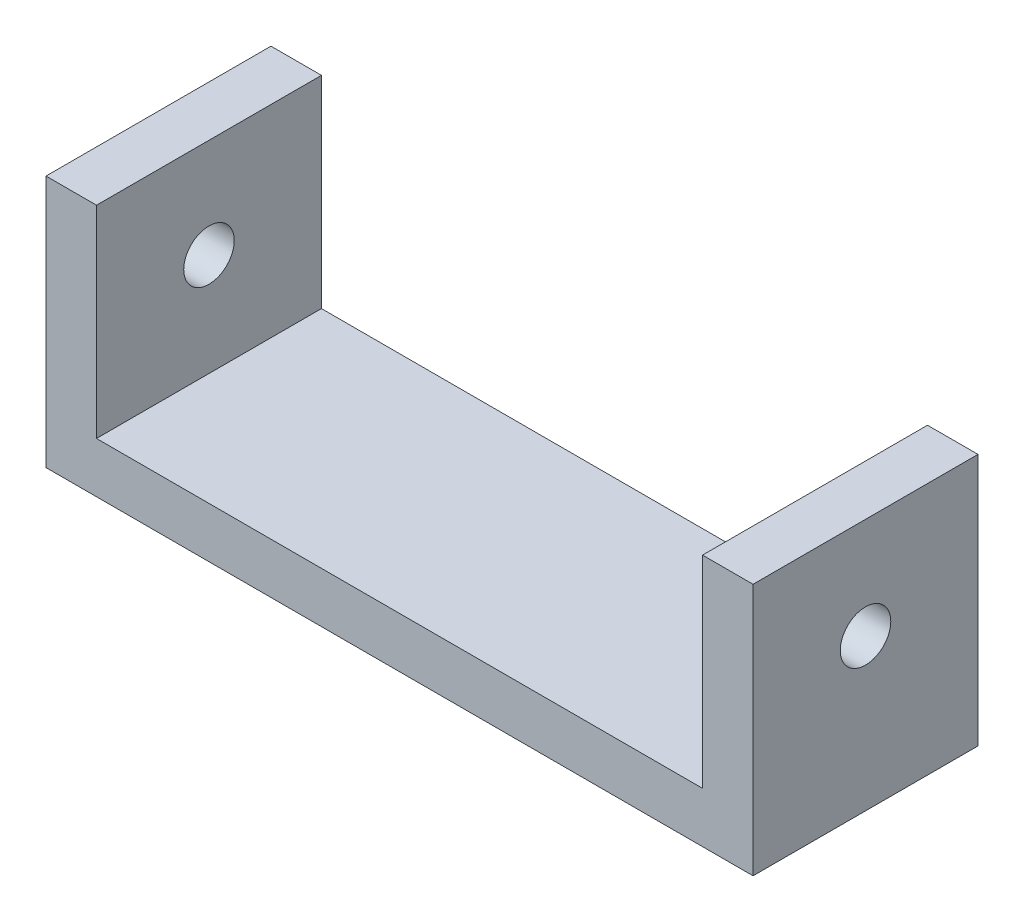
SolidWorks part; units mm, degrees
ref_plane "Front Plane" through (0, 0, 0) normal (0, 0, 1) x (1, 0, 0)
ref_plane "Top Plane" through (0, 0, 0) normal (0, 1, 0) x (1, 0, 0)
ref_plane "Right Plane" through (0, 0, 0) normal (1, 0, 0) x (0, 0, -1)
sketch "Sketch1" plane through (0, 0, 0) normal (0, 1, 0) x (1, 0, 0)
  line L1 (-44.45, 14.1421) -> (44.45, 14.1421)
  line L2 (-44.45, 14.1421) -> (-44.45, -14.1421)
  line L3 (-44.45, -14.1421) -> (44.45, -14.1421)
  line L4 (44.45, 14.1421) -> (44.45, -14.1421)
  line L5 (-44.45, 14.1421) -> (44.45, -14.1421) construction
  line L6 (-44.45, -14.1421) -> (44.45, 14.1421) construction
  point P0 (0, 0)
  dimension "D1" = 88.9
extrude "Boss-Extrude1" add sketch "Sketch1" along normal blind 6.35
sketch "Sketch2" plane through (0, 6.35, 0) normal (0, 1, 0) x (1, 0, 0)
  line L0 (-44.45, -14.1421) -> (44.45, -14.1421) construction
  line L1 (-44.45, 14.1421) -> (-38.1, 14.1421)
  line L2 (-44.45, 14.1421) -> (-44.45, -14.1421)
  line L3 (-44.45, -14.1421) -> (-38.1, -14.1421)
  line L4 (-38.1, 14.1421) -> (-38.1, -14.1421)
  line L6 (44.45, 14.1421) -> (38.1, 14.1421)
  line L7 (44.45, 14.1421) -> (44.45, -14.1421)
  line L8 (44.45, -14.1421) -> (38.1, -14.1421)
  line L9 (38.1, 14.1421) -> (38.1, -14.1421)
  dimension "D1" = 6.35
  dimension "D2" = 6.35
extrude "Boss-Extrude2" add sketch "Sketch2" along normal blind 25.4
sketch "Sketch3" plane through (-44.45, 0, 0) normal (-1, 0, 0) x (0, 0, 1)
  line L0 (-14.1421, 6.7458) -> (14.1421, 31.75) construction
  line L1 (-14.1421, 31.75) -> (-14.1421, 0) construction
  line L2 (-14.1421, 31.75) -> (14.1421, 6.7458) construction
  line L3 (14.1421, 31.75) -> (14.1421, 0) construction
  circle A0 centre (0, 19.2479) radius 3.175
  dimension "D1" = 6.35
extrude "Cut-Extrude1" cut sketch "Sketch3" against normal blind 6.35
sketch "Sketch4" plane through (44.45, 0, 0) normal (1, 0, 0) x (0, 0, -1)
  line L0 (-14.1421, 6.35) -> (14.1421, 31.75) construction
  line L1 (-14.1421, 31.75) -> (14.1421, 6.35) construction
  circle A0 centre (0, 19.05) radius 3.175
  dimension "D1" = 6.35
extrude "Cut-Extrude2" cut sketch "Sketch4" against normal blind 7.62 contours A0
